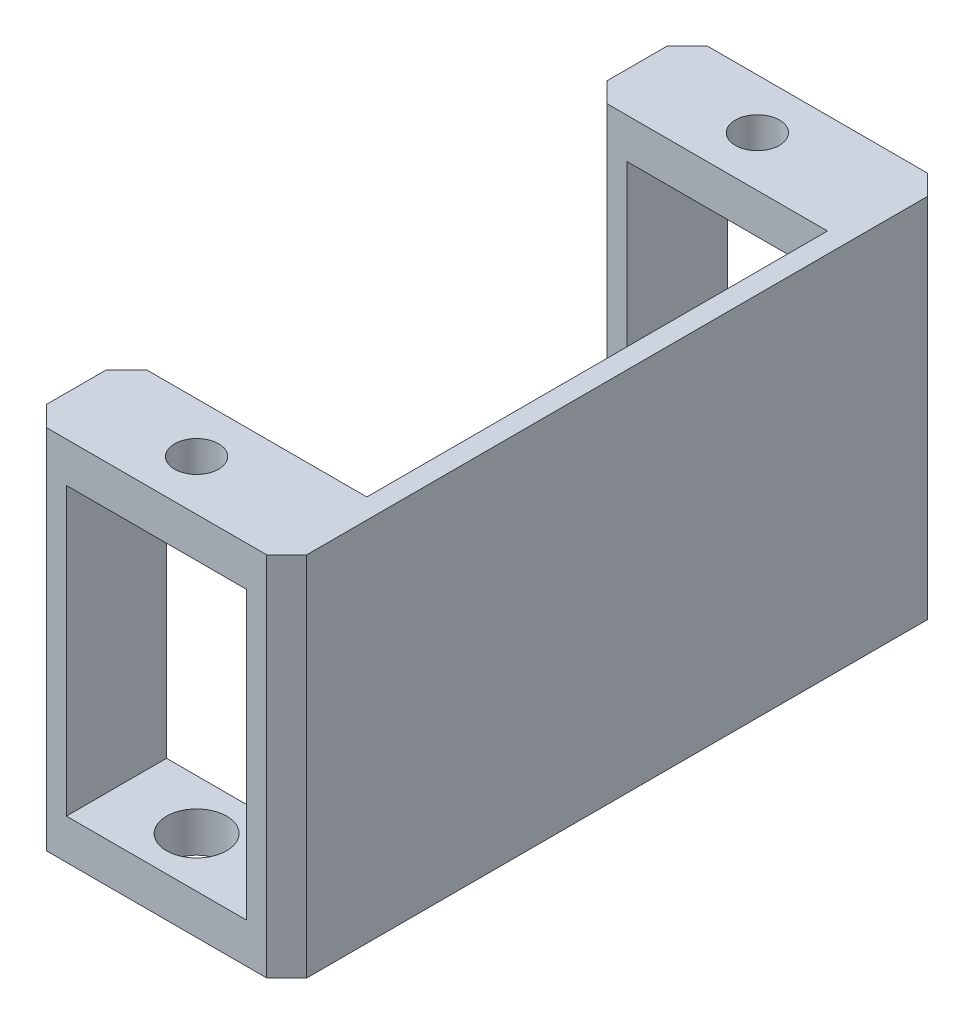
SolidWorks part; units mm, degrees
ref_plane "前基準面" through (0, 0, 0) normal (0, 0, 1) x (1, 0, 0)
ref_plane "上基準面" through (0, 0, 0) normal (0, 1, 0) x (1, 0, 0)
ref_plane "右基準面" through (0, 0, 0) normal (1, 0, 0) x (0, 0, -1)
sketch "Sketch1" plane through (0, 0, 0) normal (0, 1, 0) x (1, 0, 0)
  line L0 (-6, -16.5) -> (6, -16.5)
  line L1 (-6, -11.5) -> (6, -11.5) construction
  line L2 (-6, -11.5) -> (-6, 11.5) construction
  line L3 (-6, 11.5) -> (6, 11.5) construction
  line L4 (6, -11.5) -> (6, 11.5) construction
  line L5 (0, 11.5) -> (0, -11.5) construction
  line L6 (-6, 0) -> (6, 0) construction
  line L7 (-6, 11.5) -> (6, 11.5)
  line L8 (-6, 11.5) -> (-6, 16.5)
  line L9 (-6, 16.5) -> (6, 16.5)
  line L10 (6, 11.5) -> (6, 16.5) construction
  line L11 (6, -11.5) -> (6, -16.5) construction
  line L12 (-6, -11.5) -> (6, -11.5)
  line L13 (-6, -11.5) -> (-6, -16.5)
  line L14 (6, 11.5) -> (6, -11.5)
  line L15 (6, 16.5) -> (7, 16.5)
  line L16 (6, 16.5) -> (6, -16.5) construction
  line L17 (6, -16.5) -> (7, -16.5)
  line L18 (7, 16.5) -> (7, -16.5)
  point P0 (0, 0)
  dimension "D1" = 23
  dimension "D2" = 12
  dimension "D3" = 5
  dimension "D4" = 1
extrude "Boss-Extrude1" add sketch "Sketch1" along normal blind 2
sketch "Sketch2" plane through (0, 2, 0) normal (0, 1, 0) x (1, 0, 0)
  line L0 (0, 11.5) -> (0, -16.5) construction
  line L1 (-6, 11.5) -> (6, 11.5) construction
  line L2 (-6, -16.5) -> (7, -16.5) construction
  line L3 (0, 0) -> (7, 0) construction
  line L4 (7, -16.5) -> (7, 16.5) construction
  line L5 (-6, -14) -> (7, -14) construction
  line L6 (-6, -11.5) -> (-6, -16.5) construction
  circle A0 centre (0, -14) radius 1.5
  circle A1 centre (0, 14) radius 1.5
  dimension "D1" = 3
extrude "Cut-Extrude1" cut sketch "Sketch2" against normal up to next
sketch "Sketch3" plane through (0, 2, 0) normal (0, 1, 0) x (1, 0, 0)
  line L0 (-6, 11.5) -> (6, 11.5) construction
  line L1 (-6, 16.5) -> (-4, 16.5)
  line L2 (-6, 16.5) -> (-6, 11.5)
  line L3 (-6, 11.5) -> (-4, 11.5)
  line L4 (-4, 16.5) -> (-4, 11.5)
  line L5 (0, 0) -> (7, 0) construction
  line L6 (7, -16.5) -> (7, 16.5) construction
  line L7 (6, 11.5) -> (6, -11.5) construction
  line L8 (7, 16.5) -> (5, 16.5)
  line L9 (7, 16.5) -> (7, 11.5)
  line L10 (7, 11.5) -> (5, 11.5) construction
  line L11 (5, 16.5) -> (5, 11.5)
  line L12 (7, 11.5) -> (6, 11.5) construction
  line L13 (7, 11.5) -> (7, -11.5)
  line L14 (7, 0) -> (6, 0) construction
  line L15 (6, 11.5) -> (6, -11.5)
  line L16 (5, 11.5) -> (6, 11.5)
  line L17 (5, -11.5) -> (6, -11.5)
  line L18 (7, -16.5) -> (7, -11.5)
  line L19 (7, -16.5) -> (5, -16.5)
  line L20 (5, -16.5) -> (5, -11.5)
  line L21 (-6, -11.5) -> (-4, -11.5)
  line L22 (-4, -16.5) -> (-4, -11.5)
  line L23 (-6, -16.5) -> (-4, -16.5)
  line L24 (-6, -16.5) -> (-6, -11.5)
  dimension "D1" = 2
  dimension "D2" = 2
extrude "Boss-Extrude2" add sketch "Sketch3" along normal blind 14.3
sketch "Sketch4" plane through (0, 16.3, 0) normal (0, 1, 0) x (1, 0, 0)
  line L0 (6, 11.5) -> (6, -11.5) construction
  line L1 (-6, -11.5) -> (-6, -16.5) construction
  line L2 (7, -16.5) -> (7, 16.5) construction
  line L3 (-6, 16.5) -> (-6, 11.5) construction
  line L4 (6, 11.5) -> (6, -11.5)
  line L5 (-6, -11.5) -> (-6, -16.5)
  line L6 (7, -16.5) -> (7, 16.5)
  line L7 (-6, 16.5) -> (-6, 11.5)
  line L8 (-6, 11.5) -> (6, 11.5)
  line L9 (-6, -11.5) -> (6, -11.5)
  line L10 (-6, -16.5) -> (7, -16.5)
  line L11 (-6, 16.5) -> (7, 16.5)
extrude "Boss-Extrude3" add sketch "Sketch4" along normal blind 2
sketch "Sketch5" plane through (0, 18.3, 0) normal (0, 1, 0) x (1, 0, 0)
  circle A0 centre (0, -14) radius 1.5 construction
  circle A1 centre (0, 14) radius 1.5 construction
  circle A2 centre (0, -14) radius 1.5 construction
  circle A3 centre (0, 14) radius 1.5 construction
  circle A4 centre (0, 14) radius 1.1
  circle A5 centre (0, -14) radius 1.1
  dimension "D1" = 2.2
extrude "Cut-Extrude2" cut sketch "Sketch5" against normal up to next
chamfer "Chamfer1" distance 1 angle 45 6 edges at (-6, 9.15, 16.5) (-6, 9.15, 11.5) (-6, 9.15, -11.5) (-6, 9.15, -16.5) (7, 9.15, -16.5) (7, 9.15, 16.5)
